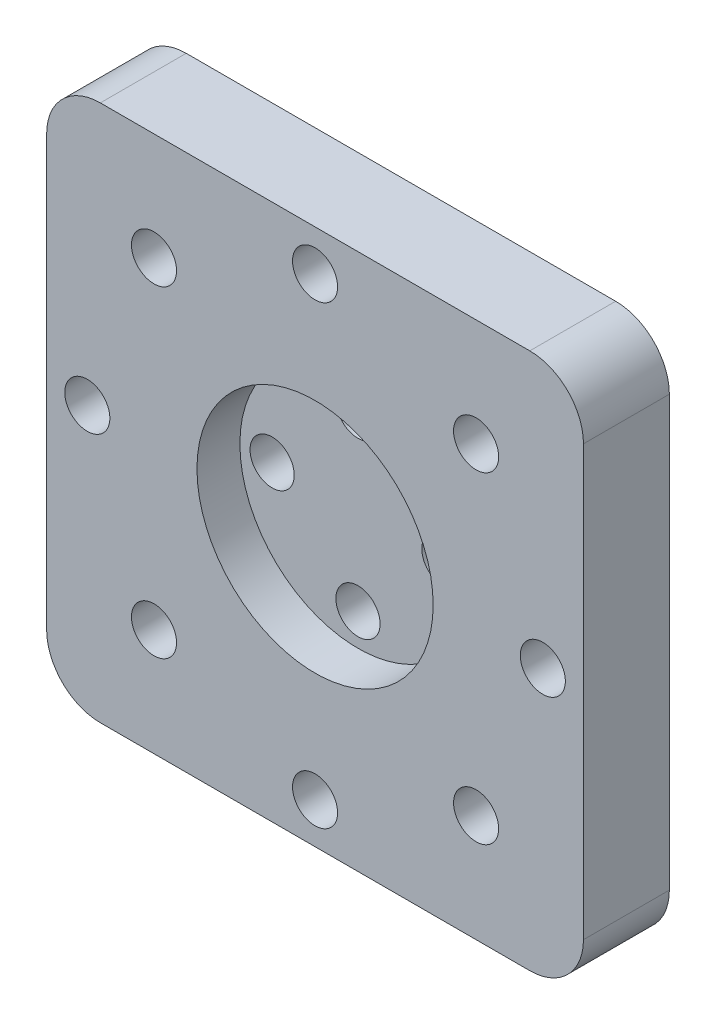
SolidWorks part; units mm, degrees
ref_plane "前视基准面" through (0, 0, 0) normal (0, 0, 1) x (1, 0, 0)
ref_plane "上视基准面" through (0, 0, 0) normal (0, 1, 0) x (1, 0, 0)
ref_plane "右视基准面" through (0, 0, 0) normal (1, 0, 0) x (0, 0, -1)
sketch "草图1" plane through (0, 0, 0) normal (0, 0, 1) x (1, 0, 0)
  line L1 (20, 25) -> (-20, 25)
  line L2 (25, 20) -> (25, -20)
  line L3 (20, -25) -> (-20, -25)
  line L4 (-25, 20) -> (-25, -20)
  circle A0 centre (0, 0) radius 14.1493
  circle A1 centre (0, 8) radius 2.0581
  circle A2 centre (8, 0) radius 2.0581
  circle A3 centre (0, -8) radius 2.0581
  circle A4 centre (-8, 0) radius 2.0581
  arc A5 (25, -20) -> (20, -25) centre (20, -20) cw
  arc A6 (-20, -25) -> (-25, -20) centre (-20, -20) cw
  arc A7 (-20, 25) -> (-25, 20) centre (-20, 20) ccw
  arc A8 (20, 25) -> (25, 20) centre (20, 20) cw
  point P21 (25, -25)
  point P26 (-25, 25)
  point P29 (25, 25)
  dimension "D5" = 5
  dimension "D1" = 50
  dimension "D2" = 50
  dimension "D3" = 25
  dimension "D4" = 25
extrude "凸台-拉伸1" add sketch "草图1" along normal blind 8 contours A8 L1 A7 L4 A6 L3 A5 L2 A0 | A0 A4 A3 A2 A1
sketch "草图2" plane through (0, 0, 8) normal (0, 0, 1) x (1, 0, 0)
  line L0 (25, 0) -> (-25, 0) construction
  line L3 (0, -25) -> (0, 25) construction
  line L6 (-25, 20) -> (-25, -20) construction
  circle A0 centre (-15, 15) radius 2.1
  circle A1 centre (-15, -15) radius 2.1
  circle A2 centre (15, -15) radius 2.1
  circle A3 centre (15, 15) radius 2.1
  circle A4 centre (21.2132, 0) radius 2.1
  circle A5 centre (0, 21.2132) radius 2.1
  circle A6 centre (-21.2132, 0) radius 2.1
  circle A7 centre (0, -21.2132) radius 2.1
  point P25 (0, 0)
  dimension "D1" = 15
  dimension "D2" = 10
  dimension "D3" = 2
extrude "切除-拉伸1" cut sketch "草图2" against normal through all
sketch "草图3" plane through (0, 0, 8) normal (0, 0, 1) x (1, 0, 0)
  circle A0 centre (0, 0) radius 11
  dimension "D1" = 22
extrude "切除-拉伸2" cut sketch "草图3" against normal blind 4
